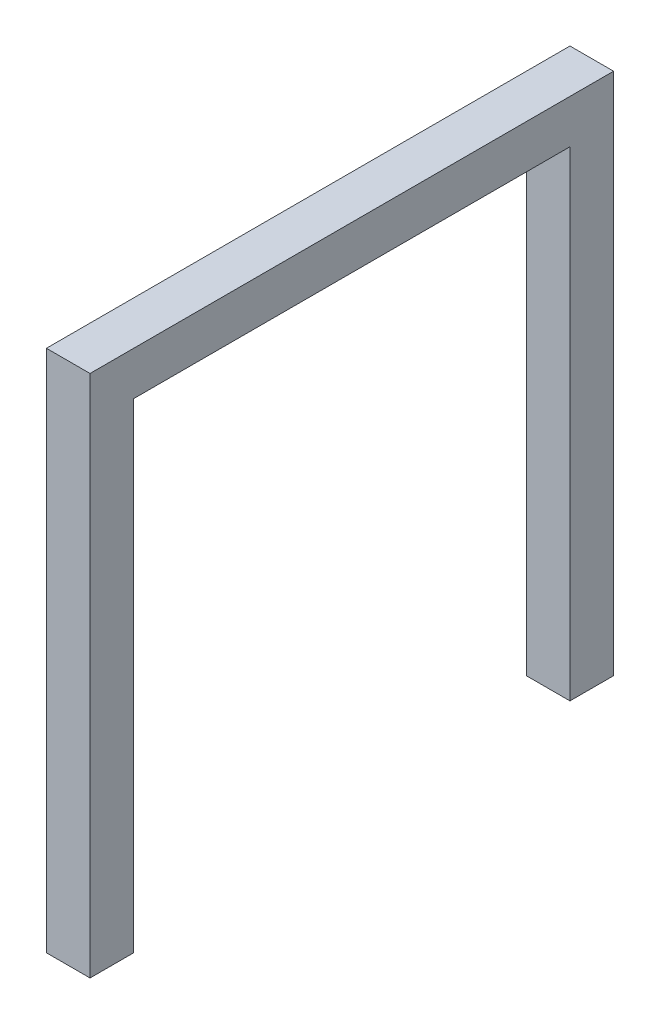
SolidWorks part; units mm, degrees
material "Oak"
ref_plane "Front Plane" through (0, 0, 0) normal (0, 0, 1) x (1, 0, 0)
ref_plane "Top Plane" through (0, 0, 0) normal (0, 1, 0) x (1, 0, 0)
ref_plane "Right Plane" through (0, 0, 0) normal (1, 0, 0) x (0, 0, -1)
sketch "Sketch1" plane through (0, 0, 0) normal (0, 0, 1) x (1, 0, 0)
  line L1 (-25, -300) -> (25, -300)
  line L2 (-25, -300) -> (-25, 300)
  line L3 (-25, 300) -> (25, 300)
  line L4 (25, -300) -> (25, 300)
  line L5 (-25, -300) -> (25, 300) construction
  line L6 (-25, 300) -> (25, -300) construction
  point P0 (0, 0)
  dimension "D1" = 50
  dimension "D2" = 600
extrude "Boss-Extrude1" add sketch "Sketch1" along normal mid plane 600
sketch "Sketch2" plane through (25, 0, 0) normal (1, 0, 0) x (0, 0, -1)
  line L0 (-300, -300) -> (300, -300) construction
  line L1 (-250, -300) -> (250, -300)
  line L2 (-250, -300) -> (-250, 250)
  line L3 (-250, 250) -> (250, 250)
  line L4 (250, -300) -> (250, 250)
  line L5 (-300, -300) -> (-300, 300) construction
  line L6 (300, -300) -> (300, 300) construction
  line L7 (-300, 300) -> (300, 300) construction
  dimension "D1" = 50
  dimension "D2" = 50
  dimension "D3" = 50
extrude "Cut-Extrude1" cut sketch "Sketch2" against normal through all both and the other way through all
